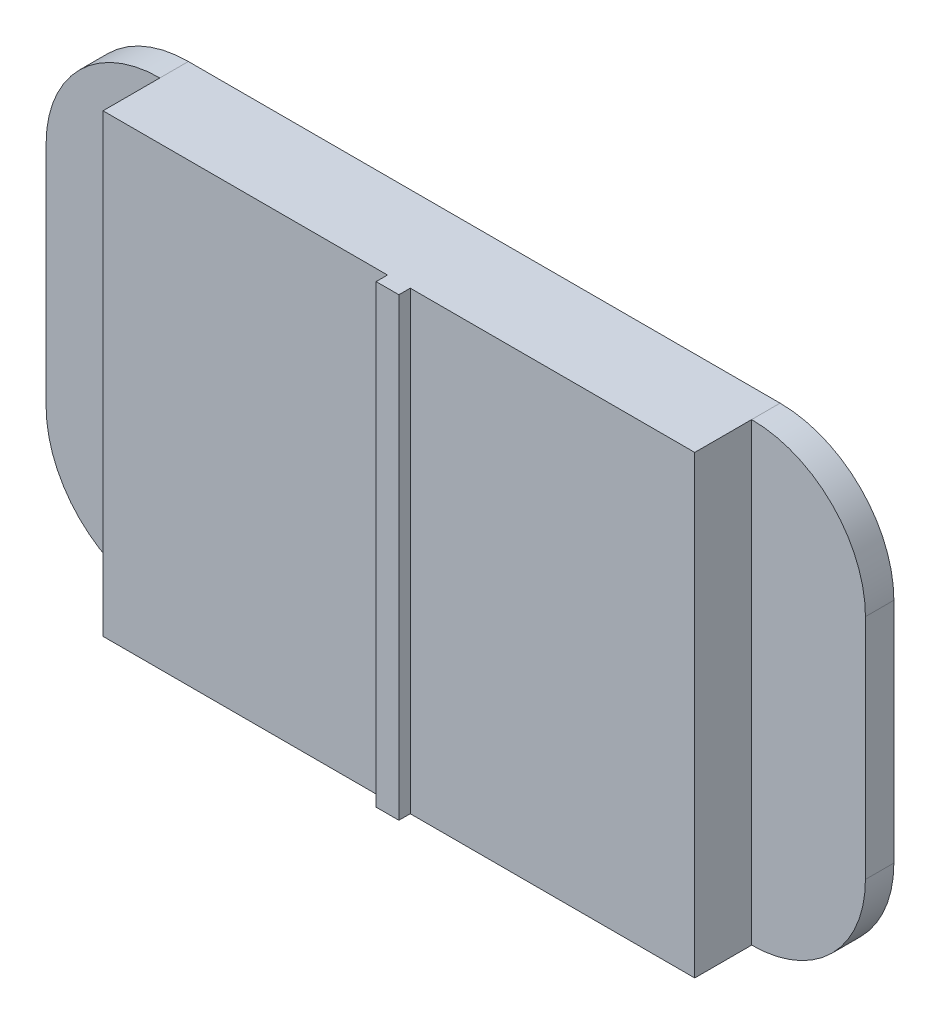
SolidWorks part; units mm, degrees
ref_plane "Спереди" through (0, 0, 0) normal (0, 0, 1) x (1, 0, 0)
ref_plane "Сверху" through (0, 0, 0) normal (0, 1, 0) x (1, 0, 0)
ref_plane "Справа" through (0, 0, 0) normal (1, 0, 0) x (0, 0, -1)
sketch "Эскиз1" plane through (0, 0, 0) normal (0, 1, 0) x (1, 0, 0)
  line L0 (-26, -14.521) -> (-26, -9.521)
  line L1 (26, -14.521) -> (1, -14.521)
  line L2 (-26, -9.521) -> (-32, -9.521)
  line L3 (32, -9.521) -> (36, -9.521)
  line L4 (0, -14.521) -> (0, 6.821) construction
  line L5 (-36, -9.521) -> (-36, -7.021)
  line L6 (36, -9.521) -> (36, -7.021)
  line L7 (1, -14.521) -> (1, -15.521)
  line L8 (1, -15.521) -> (-1, -15.521)
  line L9 (-1, -15.521) -> (-1, -14.521)
  line L10 (1, -7.021) -> (36, -7.021)
  line L11 (1, -7.021) -> (-1, -7.021)
  line L12 (-1, -14.521) -> (-26, -14.521)
  line L14 (26, -9.521) -> (32, -9.521)
  line L15 (26, -14.521) -> (26, -9.521)
  line L16 (-36, -7.021) -> (-1, -7.021)
  line L17 (-32, -9.521) -> (-36, -9.521)
  point P0 (0, 0)
  point P9 (-1, -7.021)
  point P12 (1, -7.021)
  dimension "D1" = 52
  dimension "D2" = 10
  dimension "D3" = 2.5
  dimension "D4" = 25
  dimension "D5" = 1
extrude "Бобышка-Вытянуть1" add sketch "Эскиз1" along normal blind 40
fillet "Скругление3" radius 10 2 edges at (-36, 40, 8.271) (-31, 40, 9.521)
fillet "Скругление6" radius 10 2 edges at (-31, 0, 9.521) (-36, 0, 8.271)
fillet "Скругление7" radius 10 2 edges at (36, 40, 8.271) (31, 40, 9.521)
fillet "Скругление8" radius 10 2 edges at (36, 0, 8.271) (31, 0, 9.521)
